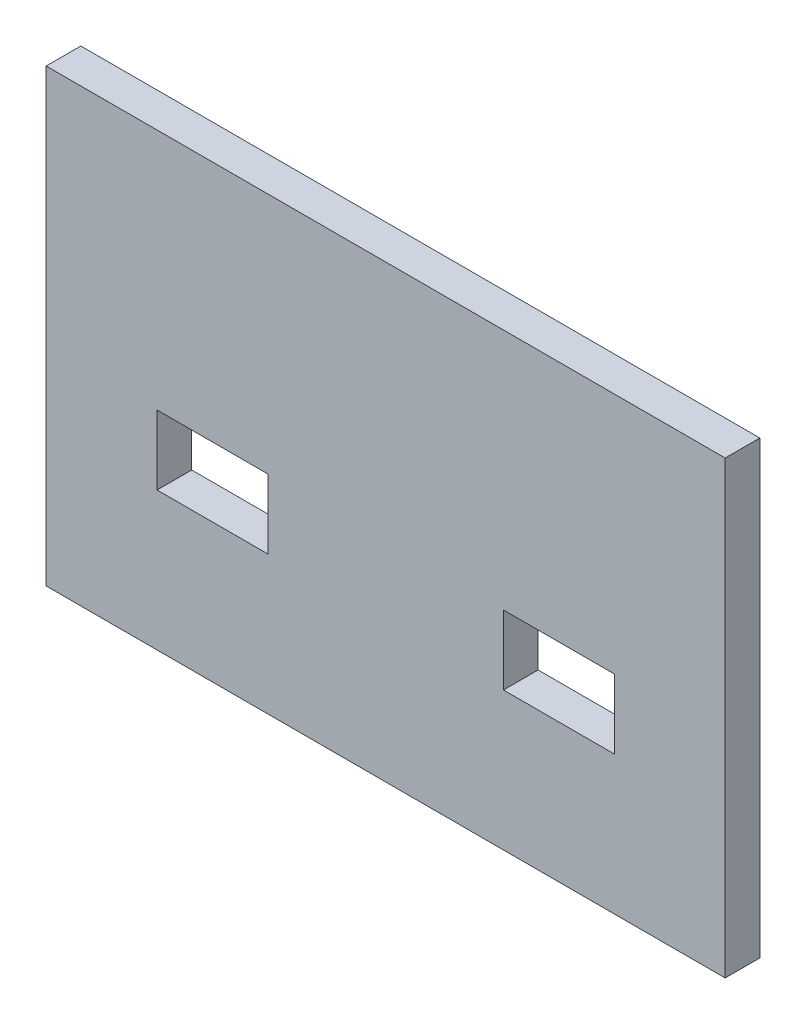
SolidWorks part; units mm, degrees
ref_plane "Front Plane" through (0, 0, 0) normal (0, 0, 1) x (1, 0, 0)
ref_plane "Top Plane" through (0, 0, 0) normal (0, 1, 0) x (1, 0, 0)
ref_plane "Right Plane" through (0, 0, 0) normal (1, 0, 0) x (0, 0, -1)
sketch "Sketch1" plane through (0, 0, 0) normal (0, 0, 1) x (1, 0, 0)
  line L1 (0, 0) -> (98, 0)
  line L2 (0, 0) -> (0, -65)
  line L3 (0, -65) -> (98, -65)
  line L4 (98, 0) -> (98, -65)
  dimension "D1" = 98
  dimension "D2" = 65
extrude "Boss-Extrude1" add sketch "Sketch1" along normal blind 5
sketch "Sketch2" plane through (0, 0, 5) normal (0, 0, 1) x (1, 0, 0)
  line L0 (98, -40) -> (74, -40)
  line L1 (98, -65) -> (82, -65)
  line L2 (98, -65) -> (98, -40)
  line L3 (98, -40) -> (82, -40)
  line L4 (82, -65) -> (82, -40)
  line L6 (66, -35) -> (82, -35)
  line L7 (66, -35) -> (66, -45)
  line L8 (66, -45) -> (82, -45)
  line L9 (82, -35) -> (82, -45)
  line L10 (66, -35) -> (82, -45) construction
  line L11 (66, -45) -> (82, -35) construction
  line L12 (16, -35) -> (32, -35)
  line L13 (16, -35) -> (16, -45)
  line L14 (16, -45) -> (32, -45)
  line L15 (32, -35) -> (32, -45)
  line L16 (16, -35) -> (32, -45) construction
  line L17 (16, -45) -> (32, -35) construction
  point P10 (24, -40)
  dimension "D1" = 25
  dimension "D2" = 16
  dimension "D3" = 24
  dimension "D4" = 10
  dimension "D5" = 16
  dimension "D6" = 34
extrude "Cut-Extrude1" cut sketch "Sketch2" against normal blind 15
